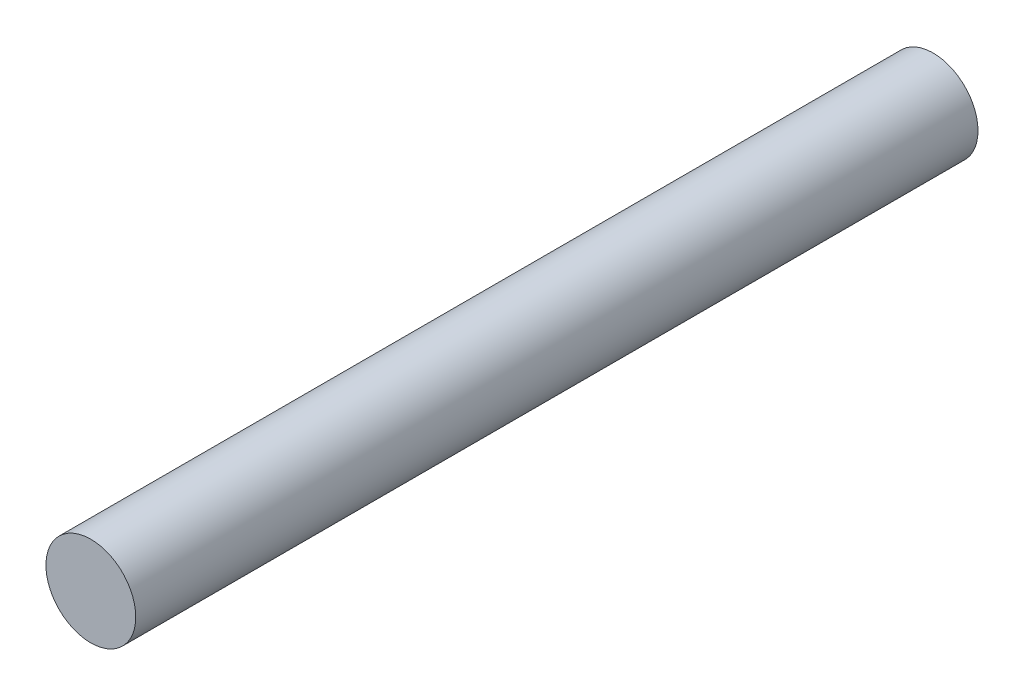
SolidWorks part; units mm, degrees
ref_plane "Front Plane" through (0, 0, 0) normal (0, 0, 1) x (1, 0, 0)
ref_plane "Top Plane" through (0, 0, 0) normal (0, 1, 0) x (1, 0, 0)
ref_plane "Right Plane" through (0, 0, 0) normal (1, 0, 0) x (0, 0, -1)
sketch "Sketch1" plane through (0, 0, 0) normal (0, 0, 1) x (1, 0, 0)
  circle A0 centre (0, 0) radius 16
  dimension "D1" = 32
extrude "Boss-Extrude1" add sketch "Sketch1" along normal blind 300
